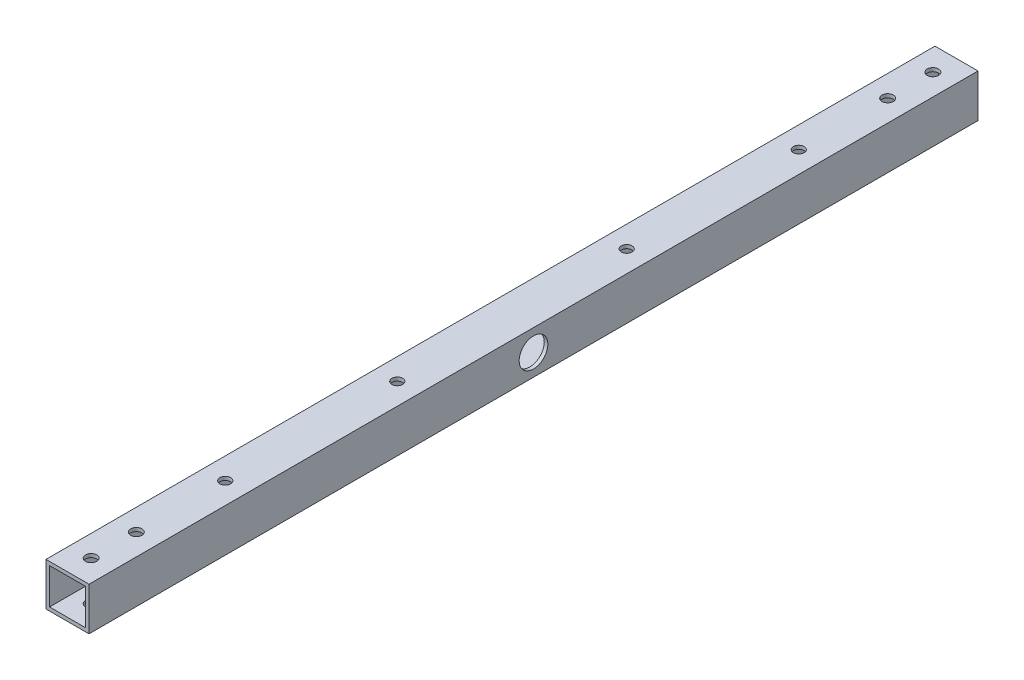
SolidWorks part; units mm, degrees
material "6061 Alloy"
ref_plane "Front Plane" through (0, 0, 0) normal (0, 0, 1) x (1, 0, 0)
ref_plane "Top Plane" through (0, 0, 0) normal (0, 1, 0) x (1, 0, 0)
ref_plane "Right Plane" through (0, 0, 0) normal (1, 0, 0) x (0, 0, -1)
sketch "Sketch1" plane through (0, 0, 0) normal (0, 0, 1) x (1, 0, 0)
  line L1 (-7.9375, -7.9375) -> (7.9375, -7.9375)
  line L2 (-7.9375, -7.9375) -> (-7.9375, 7.9375)
  line L3 (-7.9375, 7.9375) -> (7.9375, 7.9375)
  line L4 (7.9375, -7.9375) -> (7.9375, 7.9375)
  line L5 (-7.9375, -7.9375) -> (7.9375, 7.9375) construction
  line L6 (-7.9375, 7.9375) -> (7.9375, -7.9375) construction
  line L7 (-9.525, -9.525) -> (9.525, -9.525)
  line L8 (-9.525, -9.525) -> (-9.525, 9.525)
  line L9 (-9.525, 9.525) -> (9.525, 9.525)
  line L10 (9.525, -9.525) -> (9.525, 9.525)
  line L11 (-9.525, -9.525) -> (9.525, 9.525) construction
  line L12 (-9.525, 9.525) -> (9.525, -9.525) construction
  point P0 (0, 0)
  point P6 (0, 0)
  dimension "D1" = 19.05
  dimension "D2" = 19.05
  dimension "D3" = 1.5875
  dimension "D4" = 1.5875
extrude "Boss-Extrude1" add sketch "Sketch1" along normal mid plane 393.7
sketch "Sketch2" plane through (0, 0, 0) normal (1, 0, 0) x (0, 0, -1)
  circle A0 centre (0, 0) radius 6.35
extrude "Cut-Extrude1" cut sketch "Sketch2" against normal through all both and the other way through all
extrude "Cut-Extrude2" cut sketch "Sketch3" against normal blind 30
sketch "Sketch3" plane through (-152.4, 13.525, 0) normal (0, 1, 0) x (1, 0, 0)
  circle A0 centre (152.4, -206.375) radius 2.5
  circle A1 centre (152.4, -186.375) radius 2.5
  circle A2 centre (152.4, -166.375) radius 2.5
  circle A3 centre (132.4, -206.375) radius 2.5
  circle A4 centre (112.4, -206.375) radius 2.5
mirror "Mirror1" of "Cut-Extrude2"
extrude "Cut-Extrude3" cut sketch "Sketch4" against normal blind 30
sketch "Sketch4" plane through (-152.4, 18.1864, 0) normal (0, 1, 0) x (1, 0, 0)
  circle A0 centre (0, 0) radius 2.3813
  circle A1 centre (152.4, -127) radius 2.3813
  circle A2 centre (152.4, 127) radius 2.3813
  circle A3 centre (152.4, -50.8) radius 2.3812
  circle A4 centre (152.4, 50.8) radius 2.3813
  circle A5 centre (0, 127) radius 2.3813
  circle A6 centre (0, -76.2) radius 2.3813
  circle A7 centre (-152.4, -127) radius 2.3813
  circle A8 centre (-152.4, 127) radius 2.3813
  circle A9 centre (-152.4, 50.8) radius 2.3813
  circle A10 centre (-152.4, -50.8) radius 2.3813
